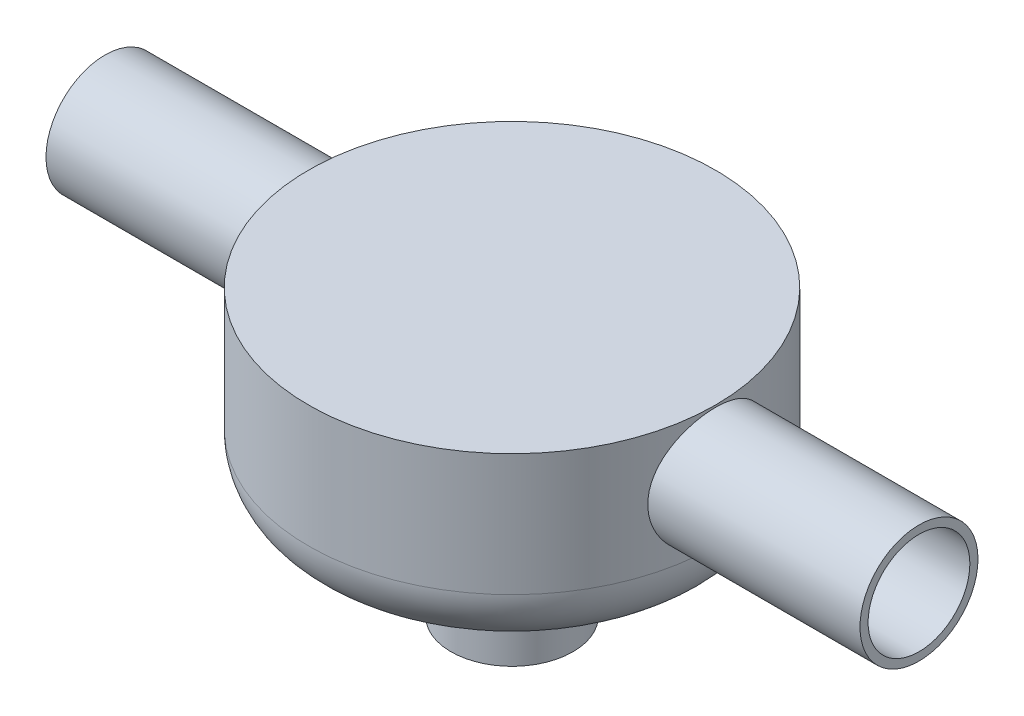
SolidWorks part; units mm, degrees
ref_plane "Front Plane" through (0, 0, 0) normal (0, 0, 1) x (1, 0, 0)
ref_plane "Top Plane" through (0, 0, 0) normal (0, 1, 0) x (1, 0, 0)
ref_plane "Right Plane" through (0, 0, 0) normal (1, 0, 0) x (0, 0, -1)
sketch "Sketch1" plane through (0, 0, 0) normal (0, 0, 1) x (1, 0, 0)
  line L0 (0, 65) -> (50, 65)
  line L1 (50, 65) -> (50, 35)
  line L2 (35, 20) -> (15, 20)
  line L3 (15, 20) -> (15, -5)
  line L5 (0, 63) -> (48, 63)
  line L6 (48, 63) -> (48, 37)
  line L7 (33, 22) -> (13, 22)
  line L10 (0, 65) -> (0, 63)
  line L12 (0, 0) -> (0, 65) construction
  line L13 (50, 65) -> (50, 20) construction
  line L14 (50, 20) -> (15, 20) construction
  line L15 (48, 63) -> (48, 22) construction
  line L16 (48, 22) -> (13, 22) construction
  line L17 (13, -2.2251) -> (0.6325, 1.8974) construction
  line L18 (15, -5) -> (0, 0) construction
  line L19 (13, 22) -> (13, -2.2251) construction
  line L20 (13, 22) -> (13, -5)
  line L21 (13, -5) -> (15, -5)
  arc A0 (50, 35) -> (35, 20) centre (35, 35) cw
  arc A1 (48, 37) -> (33, 22) centre (33, 37) cw
  point P16 (50, 20)
  dimension "D7" = 15
  dimension "D1" = 50
  dimension "D2" = 30
  dimension "D3" = 25
  dimension "D4" = 65
  dimension "D5" = 15
  dimension "D6" = 2
revolve "Revolve1" add sketch "Sketch1" angle 360 about L12
sketch "Sketch2" plane through (0, 0, 0) normal (1, 0, 0) x (0, 0, -1)
  line L2 (50, 65) -> (-50, 65) construction
  circle A0 centre (0, 50) radius 12.5
  dimension "D1" = 25
  dimension "D2" = 15
extrude "Cut-Extrude1" cut sketch "Sketch2" against normal through all both and the other way through all contours A0
ref_plane "Plane1" through (0, 35, 0) normal (0, 1, 0) x (1, 0, 0)
ref_plane "Plane4" through (100, 0, 0) normal (1, 0, 0) x (0, 0, -1)
sketch "Sketch12" plane through (100, 0, 0) normal (1, 0, 0) x (0, 0, -1)
  circle A0 centre (0, 50) radius 12.5 construction
  circle A1 centre (0, 50) radius 12.5
extrude "Extrude-Thin1" add sketch "Sketch12" against normal up to surface (52.1487 mm away) thin contours A1
mirror "Mirror1" about plane through (0, 0, 0) normal (1, 0, 0) of "Extrude-Thin1"
